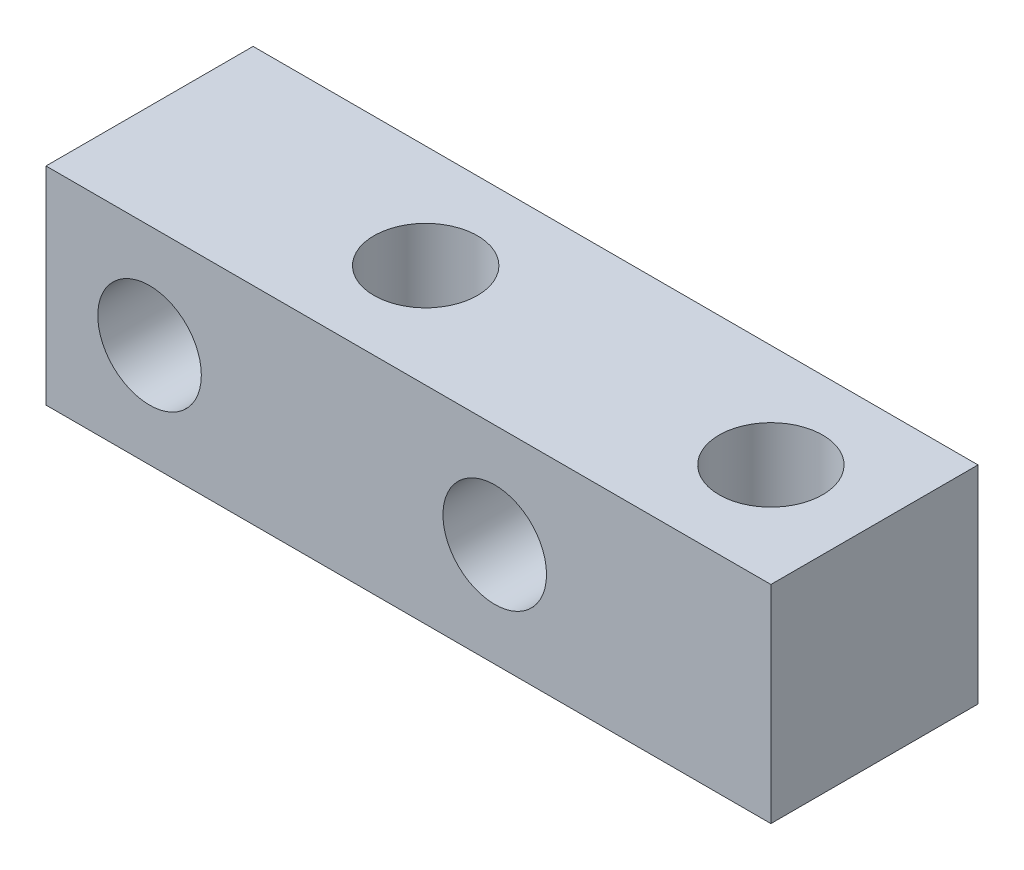
SolidWorks part; units mm, degrees
material "6系铝"
ref_plane "前视基准面" through (0, 0, 0) normal (0, 0, 1) x (1, 0, 0)
ref_plane "上视基准面" through (0, 0, 0) normal (0, 1, 0) x (1, 0, 0)
ref_plane "右视基准面" through (0, 0, 0) normal (1, 0, 0) x (0, 0, -1)
sketch "草图1" plane through (0, 0, 0) normal (0, 0, 1) x (1, 0, 0)
  line L0 (-10.5, 0) -> (10.5, 0) construction
  line L1 (-10.5, 3) -> (10.5, 3)
  line L2 (-10.5, 3) -> (-10.5, -3)
  line L3 (-10.5, -3) -> (10.5, -3)
  line L4 (10.5, 3) -> (10.5, -3)
  line L5 (-10.5, 3) -> (10.5, -3) construction
  line L6 (-10.5, -3) -> (10.5, 3) construction
  circle A0 centre (-7.5, 0) radius 1.5
  circle A1 centre (2.5, 0) radius 1.5
  point P0 (0, 0)
  dimension "D3" = 3
  dimension "D4" = 3
  dimension "D5" = 3
  dimension "D6" = 10
  dimension "D1" = 21
  dimension "D2" = 6
extrude "凸台-拉伸1" add sketch "草图1" along normal blind 6
sketch "草图2" plane through (0, 3, 0) normal (0, 1, 0) x (1, 0, 0)
  line L0 (10.5, -3) -> (-10.5, -3) construction
  line L1 (10.5, -6) -> (10.5, 0) construction
  line L2 (-10.5, -6) -> (-10.5, 0) construction
  circle A0 centre (7.5, -3) radius 1.5
  circle A1 centre (-2.5, -3) radius 1.5
  dimension "D1" = 3
  dimension "D2" = 3
  dimension "D4" = 10
  dimension "D3" = 3
extrude "切除-拉伸1" cut sketch "草图2" against normal blind 8
